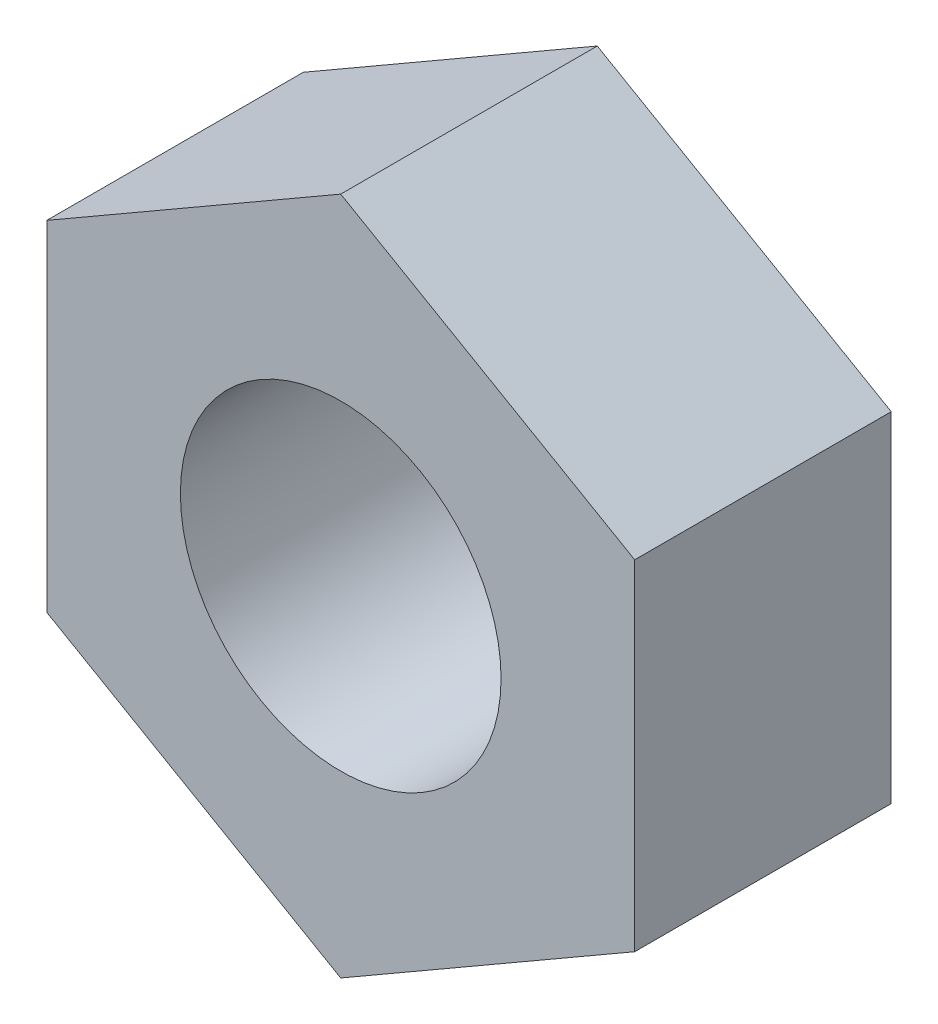
SolidWorks part; units mm, degrees
ref_plane "Plan de face" through (0, 0, 0) normal (0, 0, 1) x (1, 0, 0)
ref_plane "Plan de dessus" through (0, 0, 0) normal (0, 1, 0) x (1, 0, 0)
ref_plane "Plan de droite" through (0, 0, 0) normal (1, 0, 0) x (0, 0, -1)
sketch "Esquisse3" plane through (0, 0, 0) normal (0, 0, 1) x (1, 0, 0)
  line L0 (0, 0) -> (0, 6.3509) construction
  line L2 (0, 0) -> (2.75, 1.5877)
  line L3 (2.75, 1.5877) -> (2.75, 4.7631)
  line L4 (2.75, 4.7631) -> (0, 6.3509)
  line L5 (0, 6.3509) -> (-2.75, 4.7631)
  line L6 (-2.75, 4.7631) -> (-2.75, 1.5877)
  line L7 (-2.75, 1.5877) -> (0, 0)
  circle A0 centre (0, 3.1754) radius 2.75 construction
  circle A1 centre (0, 3.1754) radius 1.5
  dimension "D2" = 3
  dimension "D1" = 5.5
extrude "Boss.-Extru.1" add sketch "Esquisse3" along normal blind 2.4
